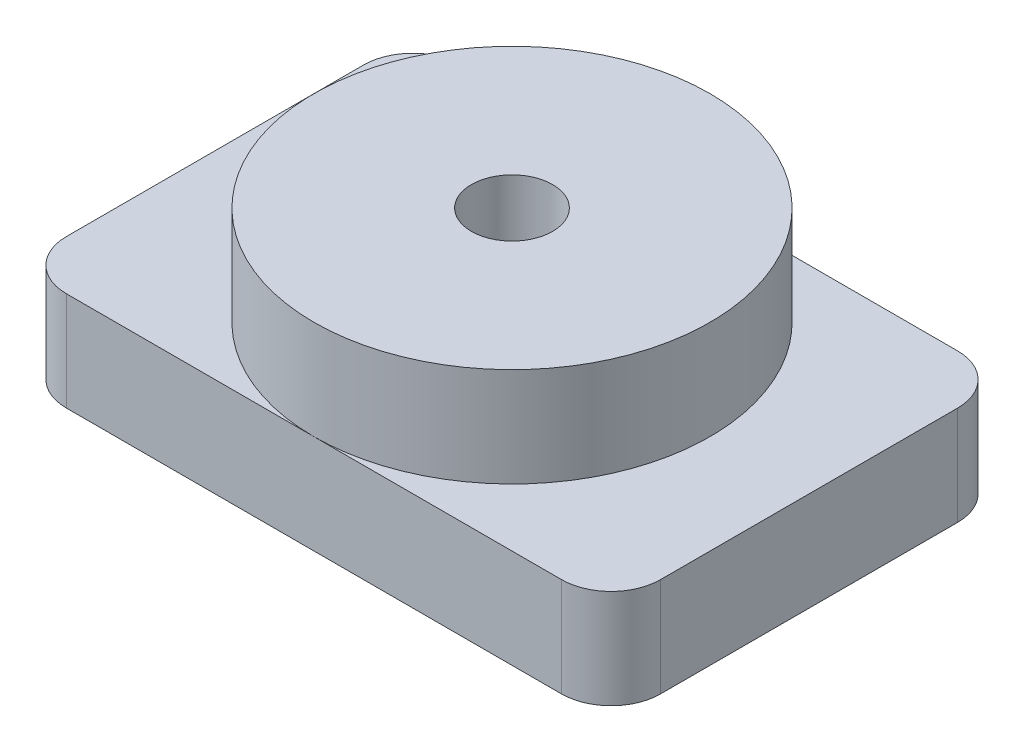
SolidWorks part; units mm, degrees
ref_plane "Front Plane" through (0, 0, 0) normal (0, 0, 1) x (1, 0, 0)
ref_plane "Top Plane" through (0, 0, 0) normal (0, 1, 0) x (1, 0, 0)
ref_plane "Right Plane" through (0, 0, 0) normal (1, 0, 0) x (0, 0, -1)
sketch "Sketch1" plane through (0, 0, 0) normal (0, 1, 0) x (1, 0, 0)
  line L1 (30, 20) -> (-30, 20)
  line L2 (30, 20) -> (30, -20)
  line L3 (30, -20) -> (-30, -20)
  line L4 (-30, 20) -> (-30, -20)
  line L5 (30, 20) -> (-30, -20) construction
  line L6 (30, -20) -> (-30, 20) construction
  point P0 (0, 0)
  dimension "D1" = 60
  dimension "D2" = 40
extrude "Boss-Extrude1" add sketch "Sketch1" along normal blind 10
sketch "Sketch2" plane through (0, 10, 0) normal (0, 1, 0) x (1, 0, 0)
  circle A0 centre (0, 0) radius 20
  dimension "D1" = 40
extrude "Boss-Extrude2" add sketch "Sketch2" along normal blind 10
sketch "Sketch4" plane through (0, 20, 0) normal (0, 1, 0) x (1, 0, 0)
  circle A0 centre (0, 0) radius 4.1
  dimension "D1" = 8.2
extrude "Cut-Extrude1" cut sketch "Sketch4" against normal through all contours A0
fillet "Fillet1" radius 5 4 edges at (-30, 5, 20) (-30, 5, -20) (30, 5, -20) (30, 5, 20)
sketch "Sketch5" plane through (0, 0, 0) normal (0, -1, 0) x (1, 0, 0)
  line L1 (-7.6788, 0) -> (-3.8394, -6.65)
  line L2 (-3.8394, -6.65) -> (3.8394, -6.65)
  line L3 (3.8394, -6.65) -> (7.6788, 0)
  line L4 (7.6788, 0) -> (3.8394, 6.65)
  line L5 (3.8394, 6.65) -> (-3.8394, 6.65)
  line L6 (-3.8394, 6.65) -> (-7.6788, 0)
  circle A0 centre (0, 0) radius 6.65 construction
  dimension "D1" = 13.3
extrude "Cut-Extrude2" cut sketch "Sketch5" against normal blind 7
